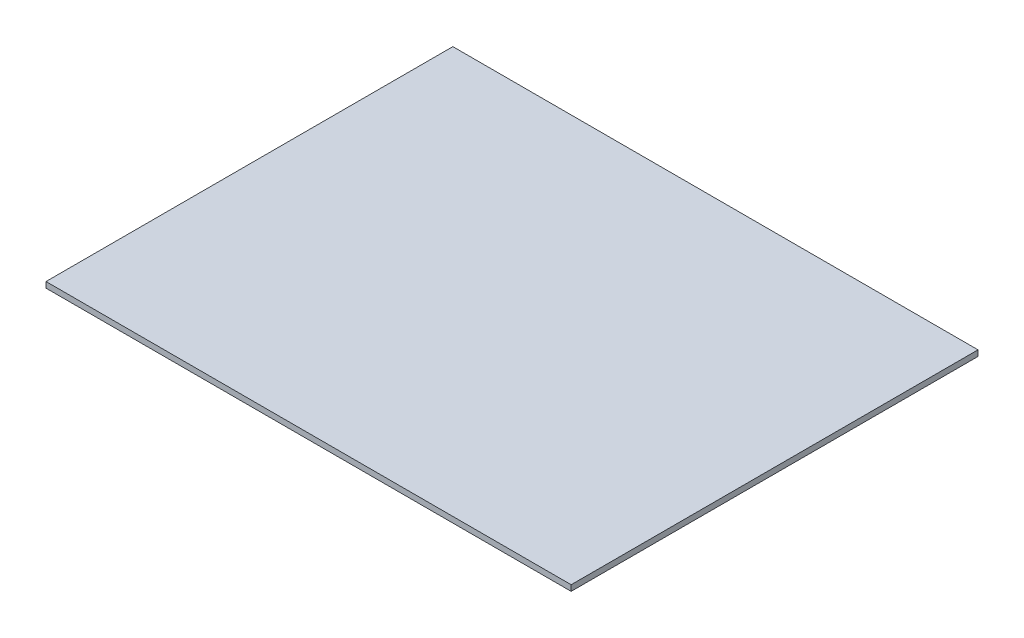
SolidWorks part; units mm, degrees
ref_plane "Front Plane" through (0, 0, 0) normal (0, 0, 1) x (1, 0, 0)
ref_plane "Top Plane" through (0, 0, 0) normal (0, 1, 0) x (1, 0, 0)
ref_plane "Right Plane" through (0, 0, 0) normal (1, 0, 0) x (0, 0, -1)
sketch "Sketch1" plane through (0, 0, 0) normal (0, 1, 0) x (1, 0, 0)
  line L1 (-91, -70.5) -> (91, -70.5)
  line L2 (-91, -70.5) -> (-91, 70.5)
  line L3 (-91, 70.5) -> (91, 70.5)
  line L4 (91, -70.5) -> (91, 70.5)
  line L5 (-91, -70.5) -> (91, 70.5) construction
  line L6 (-91, 70.5) -> (91, -70.5) construction
  point P0 (0, 0)
  dimension "D1" = 182
  dimension "D2" = 141
extrude "Boss-Extrude1" add sketch "Sketch1" along normal blind 2
